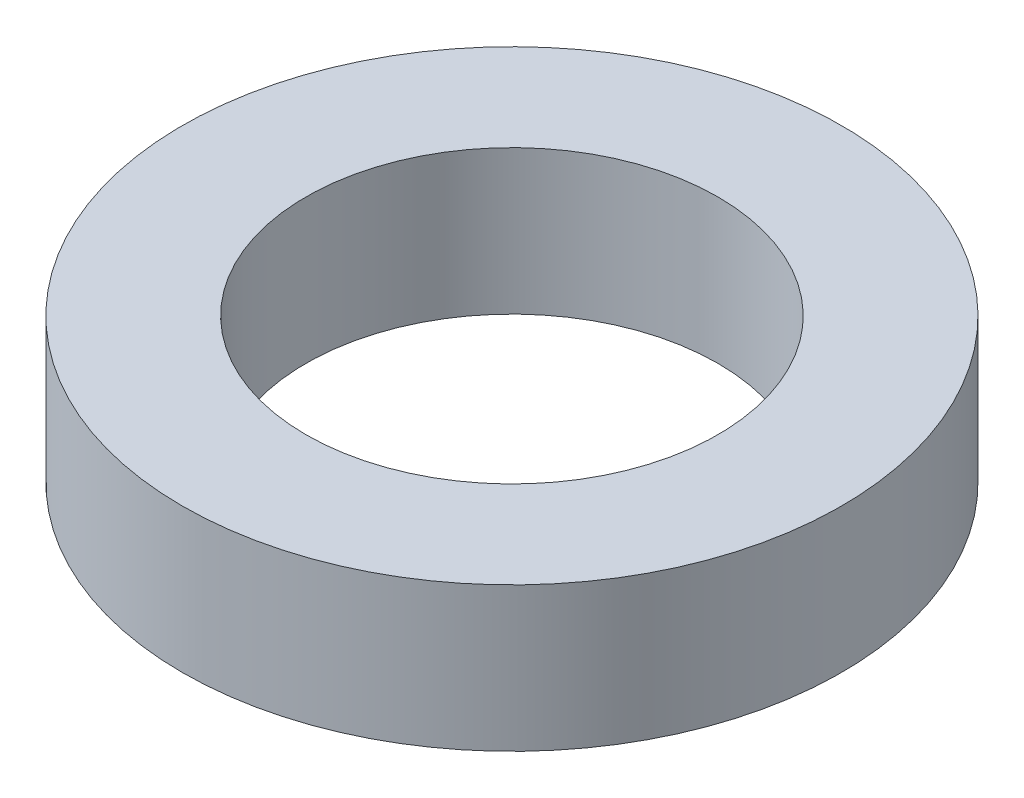
SolidWorks part; units mm, degrees
ref_plane "Front Plane" through (0, 0, 0) normal (0, 0, 1) x (1, 0, 0)
ref_plane "Top Plane" through (0, 0, 0) normal (0, 1, 0) x (1, 0, 0)
ref_plane "Right Plane" through (0, 0, 0) normal (1, 0, 0) x (0, 0, -1)
sketch "Sketch1" plane through (0, 0, 0) normal (0, 1, 0) x (1, 0, 0)
  circle A0 centre (0, 0) radius 16
  circle A1 centre (0, 0) radius 10
  dimension "D1" = 20
  dimension "D2" = 32
extrude "Boss-Extrude1" add sketch "Sketch1" along normal mid plane 7
equation "\"Ns\" = 48"
equation "\"Np_b\" = 40"
equation "\"Np_s\" = 28"
equation "\"Nr_b\" = 128"
equation "\"num_planet\" = 4"
equation "\"module\" = 0.6"
equation "\"fw_p_b\" = 12.445965467317981"
equation "\"fw_r_b\" = 12.445965467317981"
equation "\"fw_s_calc\" = 2.359230083666351"
equation "\"fw_r_s\" = 10.1295029769434"
equation "\"fw_p_s\" = 11.6295029769434"
equation "\"fw_s_used\" = 31.575468444261382"
equation "\"pressure_angle\" = 20.0"
equation "\"motor_OD\" = 72"
equation "\"motor_height\" = 27"
equation "\"motor_mount_hole_PCD\" = 32"
equation "\"motor_mount_hole_dia\" = 4"
equation "\"motor_mount_hole_num\" = 4"
equation "\"wire_slot_dist_from_center\" = 26"
equation "\"wire_slot_length\" = 10"
equation "\"wire_slot_radius\" = 2.5"
equation "\"motor_output_hole_PCD\" = 22"
equation "\"motor_output_hole_dia\" = 3"
equation "\"motor_output_hole_num\" = 4"
equation "\"h_a\" = 0.6"
equation "\"h_f\" = 0.75"
equation "\"clr_tip_root\" = 0.15000000000000002"
equation "\"dp_r_b\" = 76.8"
equation "\"db_r_b\" = 72.16839327635776"
equation "\"alpha_r_b\" = 0.8539582918412556"
equation "\"beta_r_b\" = 3.114166583682511"
equation "\"bearing_ID\" = 65"
equation "\"bearing_OD\" = 85"
equation "\"bearing_height\" = 10"
equation "\"clearance_planet\" = 1.5"
equation "\"case_dist\" = 6.5"
equation "\"Motor_case_OD_max\" = 115.5"
equation "\"case_mounting_PCD\" = 108.0"
equation "\"bearing mount thickness\" = 8"
equation "\"case_mounting_hole_dia\" = 3"
equation "\"output_mounting_PCD\" = 93"
equation "\"output_mounting_hole_dia\" = 4"
equation "\"clearance_case_mount_holes_shell_thickness\" = 1"
equation "\"motor_case_OD_base\" = 106.0"
equation "\"sec_carrier_thickness\" = 5"
equation "\"sun_coupler_hub_thickness\" = 4"
equation "\"clearance_sun_coupler_sec_carrier\" = 1.5"
equation "\"clearance_motor_and_case\" = 14.5"
equation "\"Motor_case_thickness\" = 2.5"
equation "\"Motor_case_ID\" = 101.0"
equation "\"case_mounting_hole_shift\" = 1.0"
equation "\"output_mounting_nut_wrench_size\" = 7"
equation "\"output_mounting_nut_thickness\" = 3.2"
equation "\"case_mounting_hole_allen_socket_dia\" = 5.5"
equation "\"output_mounting_nut_depth\" = 3"
equation "\"case_mounting_bolt_depth\" = 4.5"
equation "\"ring_radial_thickness\" = 5"
equation "\"ring_OD_b\" = 86.8"
equation "\"ring_to_chamfer_clearance\" = 1.5"
equation "\"Motor_case_OD_base_to_chamfer\" = 5"
equation "\"pattern_offset_from_motor_case_OD_base\" = 3"
equation "\"pattern_bulge_dia\" = 3"
equation "\"pattern_num_bulge\" = 18"
equation "\"pattern_depth\" = 2"
equation "\"case_mounting_wrench_size\" = 5.5"
equation "\"case_mounting_nut_clearance\" = 2"
equation "\"base_plate_thickness\" = 4"
equation "\"case_mounting_nut_thickness\" = 2.4"
equation "\"case_mounting_surface_height\" = 4"
equation "\"central_hole_offset_from_motor_mount_PCD\" = 5"
equation "\"driver_upper_holes_dist_from_center\" = 29"
equation "\"driver_lower_holes_dist_from_center\" = 13"
equation "\"driver_side_holes_dist_from_center\" = 22.5"
equation "\"driver_mount_holes_dia\" = 3"
equation "\"driver_mount_inserts_OD\" = 4.8"
equation "\"driver_mount_thickness\" = 1.5"
equation "\"driver_mount_height\" = 6"
equation "\"air_flow_hole_offset\" = 3"
equation "\"pressure angle\" = 20.0"
equation "\"h_b\" = 0.75"
equation "\"planet_pin_bolt_dia\" = 5"
equation "\"planet_pin_socket_head_dia\" = 8.5"
equation "\"carrier_PCD\" = 52.8"
equation "\"planet_shaft_dia\" = 8"
equation "\"planet_shaft_step_offset\" = 1"
equation "\"carrier_trapezoidal_support_sun_offset\" = 5"
equation "\"carrier_trapezoidal_support_hole_PCD_offset_bearing_ID\" = 4"
equation "\"carrier_trapezoidal_support_hole_dia\" = 3"
equation "\"carrier_trapezoidal_support_hole_socket_head_dia\" = 5.5"
equation "\"carrier_bearing_step_width\" = 1.5"
equation "\"standard_clearance_1_5mm\" = 1.5"
equation "\"standard_fillet_1_5mm\" = 1.5"
equation "\"sun_shaft_bearing_ID\" = 8"
equation "\"sun_shaft_bearing_OD\" = 16"
equation "\"sun_shaft_bearing_width\" = 5"
equation "\"standard_bearing_insertion_chamfer\" = 0.5"
equation "\"carrier_trapezoidal_support_hole_wrench_size\" = 5.5"
equation "\"planet_pin_bolt_wrench_size\" = 8"
equation "\"planet_bearing_OD\" = 12"
equation "\"planet_bearing_width\" = 3.5"
equation "\"planet_bore\" = 10"
equation "\"dp_s\" = 28.799999999999997"
equation "\"db_s\" = 27.06314747863416"
equation "\"alpha_s\" = 0.8539582918412343"
equation "\"beta_s\" = 2.0420834163175314"
equation "\"dp_p_b\" = 24.0"
equation "\"db_p_b\" = 22.552622898861802"
equation "\"alpha_p_b\" = 0.8539582918412414"
equation "\"beta_p_b\" = 2.792083416317517"
equation "\"sun_hub_dia\" = 28.0"
equation "\"sun_central_bolt_dia\" = 5"
equation "\"sun_central_bolt_socket_head_dia\" = 8.5"
equation "\"motor_output_hole_CSK_OD\" = 6"
equation "\"motor_output_hole_CSK_head_height\" = 1.5"
equation "\"bearing_retainer_thickness\" = 2"
equation "\"dp_p_s\" = 16.8"
equation "\"db_p_s\" = 15.786836029203263"
equation "\"alpha_p_s\" = 0.8539582918412343"
equation "\"beta_p_s\" = 4.72065484488896"
equation "\"Nr_s\" = 116"
equation "\"clr_tip_root_s\" = 0.15000000000000002"
equation "\"dp_r_s\" = 69.6"
equation "\"db_r_s\" = 65.40260640669922"
equation "\"alpha_r_s\" = 0.8539582918412343"
equation "\"beta_r_s\" = 3.2596407216135033"
equation "\"small_ring_case_thickness\" = 4"
equation "\"carrier_thickness\" = 4"
equation "\"small_ring_output_wall_thickness\" = 5"
equation "\"small_ring_output_wall_to_bearing_shaft_attachement_hole_dia\" = 4"
equation "\"small_ring_output_wall_to_bearing_shaft_attachement_hole_depth\" = 6.5"
equation "\"small_ring_output_wall_to_bearing_shaft_attachement_nut_wrench\" = 7"
equation "\"small_ring_output_wall_to_bearing_shaft_attachement_nut_thickness\" = 3.2"
equation "\"small_ring_output_wall_to_bearing_shaft_attachement_hole_pcd\" = 12"
equation "\"small_ring_output_wall_to_bearing_shaft_attachement_hole_num\" = 3"
equation "\"small_ring_output_wall_to_bearing_shaft_attachement_hole_CSK_OD\" = 8"
equation "\"small_ring_output_wall_to_bearing_shaft_attachement_hole_CSK_head_height\" = 2.0"
equation "\"carrier_small_ring_inner_bearing_ID\" = 20"
equation "\"carrier_small_ring_inner_bearing_OD\" = 32"
equation "\"carrier_small_ring_inner_bearing_height\" = 7"
equation "\"carrier_small_ring_inner_bearing_flap\" = 2"
equation "\"D1@Boss-Extrude1\"=\"carrier_small_ring_inner_bearing_height\""
equation "\"D1@Sketch1\"=\"carrier_small_ring_inner_bearing_ID\""
equation "\"D2@Sketch1\"=\"carrier_small_ring_inner_bearing_OD\""
